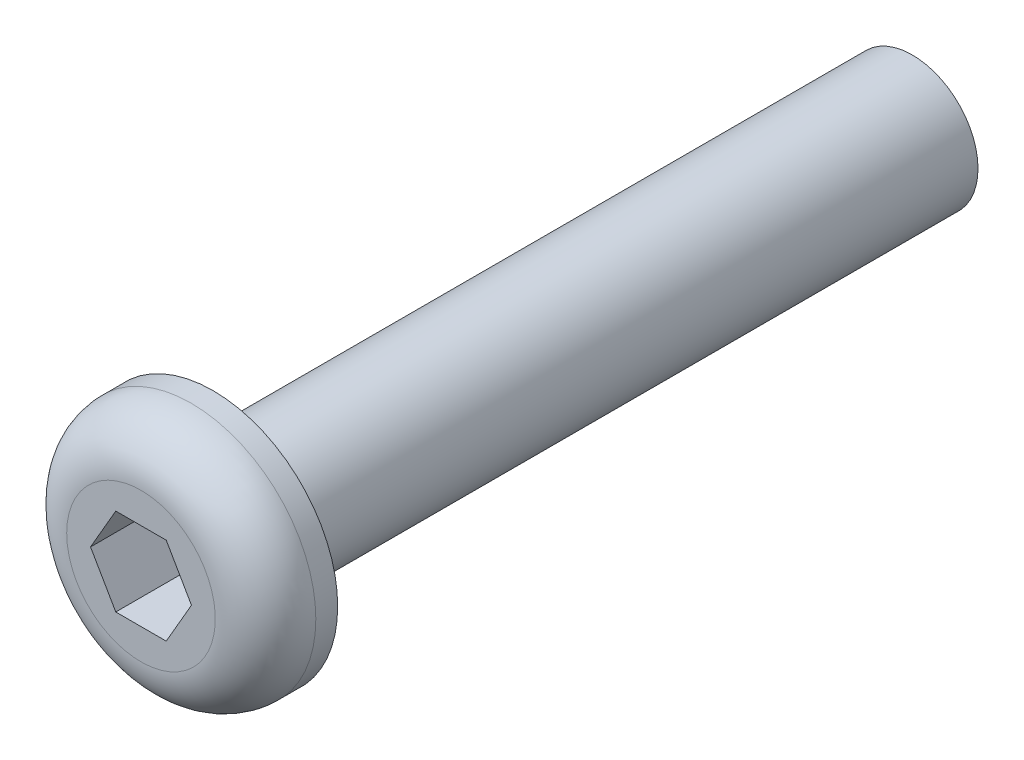
SolidWorks part; units mm, degrees
material "AISI 304"
ref_plane "Front Plane" through (0, 0, 0) normal (0, 0, 1) x (1, 0, 0)
ref_plane "Top Plane" through (0, 0, 0) normal (0, 1, 0) x (1, 0, 0)
ref_plane "Right Plane" through (0, 0, 0) normal (1, 0, 0) x (0, 0, -1)
sketch "Sketch1" plane through (0, 0, 0) normal (0, 0, 1) x (1, 0, 0)
  circle A0 centre (0, 0) radius 1.5
  dimension "D1" = 3
extrude "Extrude1" add sketch "Sketch1" against normal blind 16
sketch "Sketch2" plane through (0, 0, 0) normal (1, 0, 0) x (0, 0, -1)
  line L0 (0, 0) -> (-10.9859, 0) construction
  line L1 (0, 0) -> (0, 2.85)
  line L2 (0, 2.85) -> (-0.5, 2.85)
  line L3 (-1.65, 0) -> (-1.65, 1.7)
  line L4 (0, 0) -> (-1.65, 0)
  arc A0 (-1.65, 1.7) -> (-0.5, 2.85) centre (-0.5, 1.7) cw
  dimension "D1" = 1.65
  dimension "D2" = 5.7
  dimension "D3" = 0.5
revolve "Revolve1" add sketch "Sketch2" angle 360 about L0
sketch "Sketch3" plane through (0, 0, 1.65) normal (0, 0, 1) x (1, 0, 0)
  line L1 (-0.5774, 1) -> (-1.1547, 0)
  line L2 (-1.1547, 0) -> (-0.5774, -1)
  line L3 (-0.5774, -1) -> (0.5774, -1)
  line L4 (0.5774, -1) -> (1.1547, 0)
  line L5 (1.1547, 0) -> (0.5774, 1)
  line L6 (0.5774, 1) -> (-0.5774, 1)
  circle A0 centre (0, 0) radius 1 construction
  dimension "D1" = 2
extrude "Cut-Extrude1" cut sketch "Sketch3" against normal blind 2
